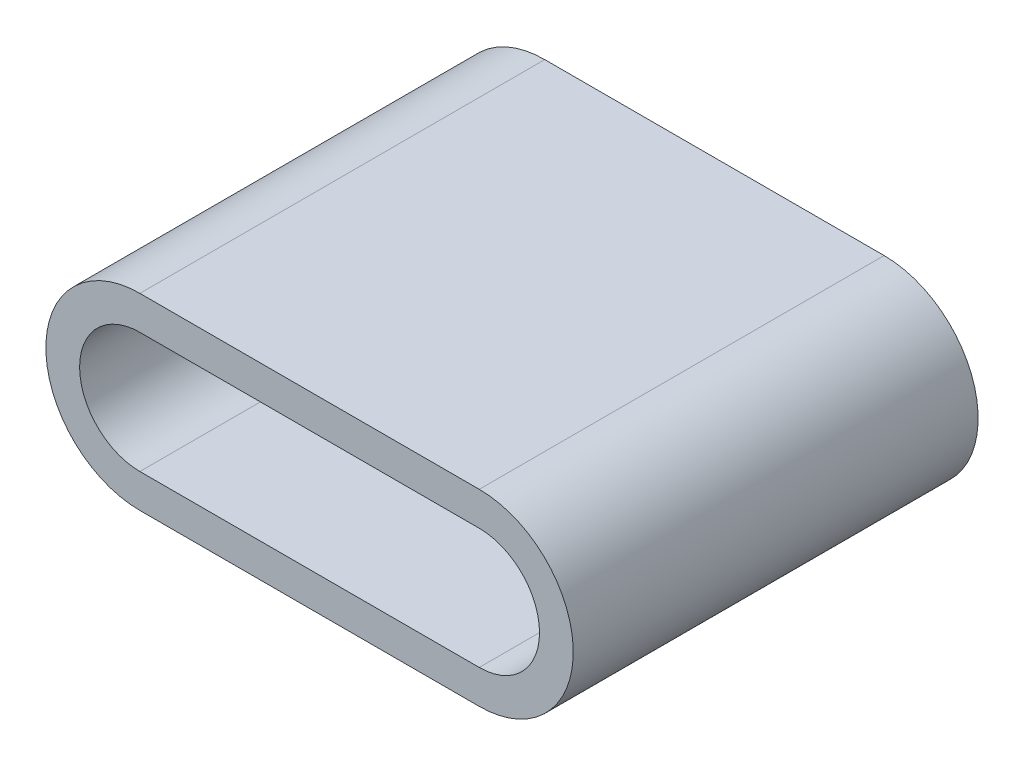
SolidWorks part; units mm, degrees
ref_plane "前视基准面" through (0, 0, 0) normal (0, 0, 1) x (1, 0, 0)
ref_plane "上视基准面" through (0, 0, 0) normal (0, 1, 0) x (1, 0, 0)
ref_plane "右视基准面" through (0, 0, 0) normal (1, 0, 0) x (0, 0, -1)
sketch "草图1" plane through (0, 0, 0) normal (0, 0, 1) x (1, 0, 0)
  line L0 (0, 0) -> (50.2907, 0) construction
  line L1 (0, 13.9307) -> (50.2907, 13.9307)
  line L2 (0, -13.9307) -> (50.2907, -13.9307)
  arc A0 (0, 13.9307) -> (0, -13.9307) centre (0, 0) ccw
  arc A1 (50.2907, -13.9307) -> (50.2907, 13.9307) centre (50.2907, 0) ccw
  point P3 (25.1453, 0)
extrude "凸台-拉伸1" add sketch "草图1" against normal blind 20 and the other way blind 10
sketch "草图6" plane through (0, 0, 10) normal (0, 0, 1) x (1, 0, 0)
  line L2 (0, -13.9307) -> (50.2907, -13.9307)
  line L3 (50.2907, 13.9307) -> (0, 13.9307)
  line L4 (0, -13.9307) -> (50.2907, -13.9307)
  line L5 (50.2907, 13.9307) -> (0, 13.9307)
  arc A2 (0, 13.9307) -> (0, -13.9307) centre (0, 0) ccw
  arc A3 (50.2907, -13.9307) -> (50.2907, 13.9307) centre (50.2907, 0) ccw
  arc A4 (0, 13.9307) -> (0, -13.9307) centre (0, 0) ccw
  arc A5 (50.2907, -13.9307) -> (50.2907, 13.9307) centre (50.2907, 0) ccw
  point P0 (50.2907, 0)
  dimension "D1" = 0
sketch "草图7" plane through (0, 0, 10) normal (0, 0, 1) x (1, 0, 0)
  line L2 (0, -13.9307) -> (50.2907, -13.9307)
  line L3 (50.2907, 13.9307) -> (0, 13.9307)
  line L4 (0, -13.9307) -> (50.2907, -13.9307)
  line L5 (50.2907, 13.9307) -> (0, 13.9307)
  arc A2 (0, 13.9307) -> (0, -13.9307) centre (0, 0) ccw
  arc A3 (50.2907, -13.9307) -> (50.2907, 13.9307) centre (50.2907, 0) ccw
  arc A4 (0, 13.9307) -> (0, -13.9307) centre (0, 0) ccw
  arc A5 (50.2907, -13.9307) -> (50.2907, 13.9307) centre (50.2907, 0) ccw
  dimension "D1" = 0
extrude "拉伸-薄壁1" add sketch "草图7" against normal up to surface (30 mm away) from offset 30 thin contours A4 L4 A5 L5
